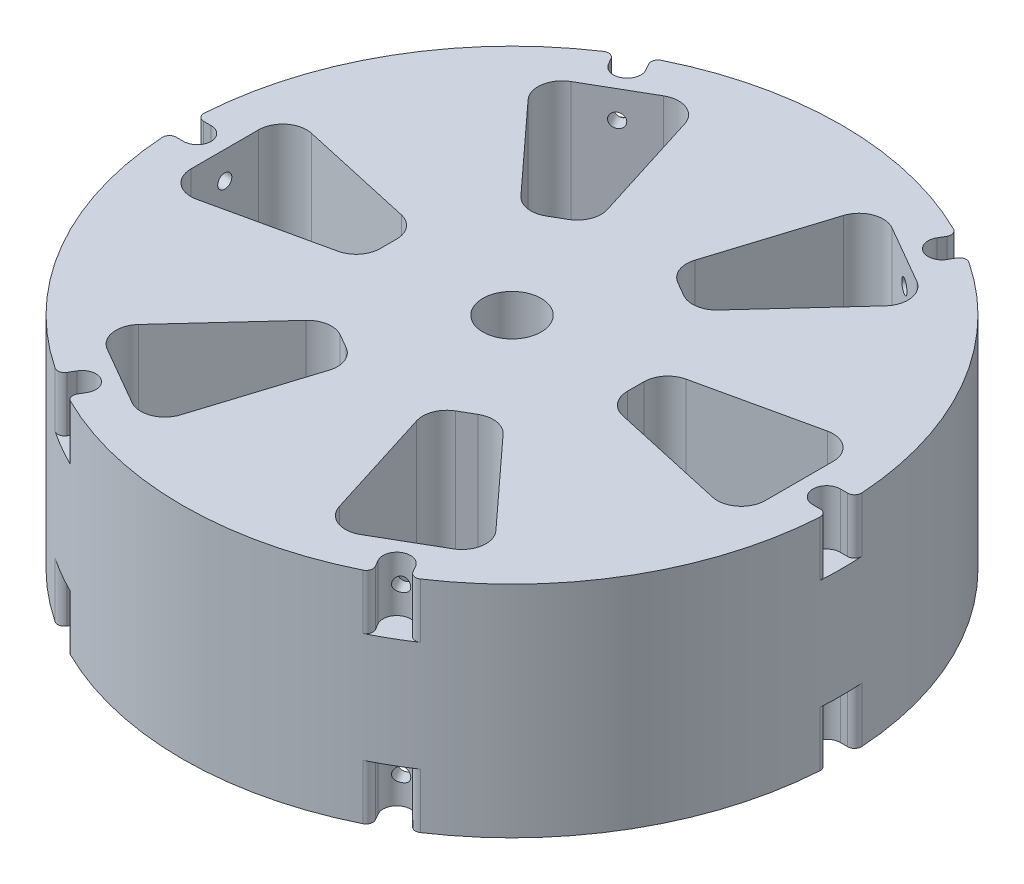
SolidWorks part; units mm, degrees
material "6061-T6 (SS)"
ref_plane "Front Plane" through (0, 0, 0) normal (0, 0, 1) x (1, 0, 0)
ref_plane "Top Plane" through (0, 0, 0) normal (0, 1, 0) x (1, 0, 0)
ref_plane "Right Plane" through (0, 0, 0) normal (1, 0, 0) x (0, 0, -1)
sketch "Sketch1" plane through (0, 0, 0) normal (0, 1, 0) x (1, 0, 0)
  circle A0 centre (0, 0) radius 76.2
  circle A1 centre (0, 0) radius 15.875
  dimension "D1" = 152.4
  dimension "D2" = 31.75
extrude "Boss-Extrude1" add sketch "Sketch1" against normal mid plane 50.8
sketch "Sketch3" plane through (0, -25.4, 0) normal (0, -1, 0) x (-1, 0, 0)
  line L0 (-76.1338, 3.175) -> (-72.771, 3.175)
  line L1 (-76.1338, -3.175) -> (-72.771, -3.175)
  circle A0 centre (0, 0) radius 76.2 construction
  arc A1 (-72.771, 3.175) -> (-72.771, -3.175) centre (-72.771, 0) cw
  arc A2 (-76.1338, -3.175) -> (-76.1338, 3.175) centre (0, 0) cw
  point P9 (-69.596, 0)
  point P13 (-76.2, 0)
  dimension "D1" = 6.35
  dimension "D2" = 6.604
extrude "Cut-Extrude1" cut sketch "Sketch3" against normal blind 12.7
sketch "Sketch4" plane through (0, -25.4, 0) normal (0, -1, 0) x (-1, 0, 0)
  line L0 (-66.421, 14.7602) -> (-66.421, -14.7602)
  line L1 (-66.421, -14.7602) -> (-28.575, -6.35)
  line L2 (-28.575, -6.35) -> (-28.575, 6.35)
  line L3 (-28.575, 6.35) -> (-66.421, 14.7602)
  line L4 (-66.421, 0) -> (0, 0) construction
  line L5 (-28.575, -6.35) -> (0, 0) construction
  circle A2 centre (0, 0) radius 15.875 construction
  point P12 (-15.875, 0)
  point P14 (-28.575, 0)
  dimension "D1" = 3.175
  dimension "D2" = 12.7
  dimension "D4" = 12.7
extrude "Cut-Extrude2" cut sketch "Sketch4" against normal through all
hole_wizard "#30 (0.1285) Diameter Hole1" positions "Sketch5" profile "Sketch6" hole size "#30" standard "ANSI Inch"
sketch "Sketch5" plane through (66.421, 0, 0) normal (-1, 0, 0) x (0, 0, 1)
  line L0 (-14.7602, -25.4) -> (14.7602, -25.4) construction
  point P0 (0, -19.05)
  dimension "D1" = 6.35
sketch "Sketch6" plane through (66.421, -19.05, 0) normal (0, 1, 0) x (0, 0, 1)
  line L0 (0, 0) -> (0, 9.779)
  line L1 (0, 9.779) -> (1.6319, 9.779)
  line L2 (1.6319, 9.779) -> (1.6319, 0)
  line L5 (1.6319, 0) -> (0, 0)
  line L11 (0, -6.35) -> (0, 107.95) construction
  dimension "Thru Hole Dia." = 3.2639
  dimension "Thru Hole Depth" = 9.779
fillet "Fillet1" radius 1.5875 2 edges at (76.1338, -19.05, 3.175) (76.1338, -19.05, -3.175)
fillet "Fillet2" radius 5.5562 4 edges at (66.421, 0, 14.7602) (66.421, 0, -14.7602) (28.575, 0, 6.35) (28.575, 0, -6.35)
mirror "Mirror1" about plane through (0, 0, 0) normal (0, 1, 0) of "Cut-Extrude1", "#30 (0.1285) Diameter Hole1"
pattern_circular "CirPattern1" count 6 over 360 about axis through (0, 0, 0) along (0, 1, 0) of "Cut-Extrude1", "Cut-Extrude2", "Fillet2", "Fillet1", "#30 (0.1285) Diameter Hole1", "Mirror1"
sketch "Sketch7" plane through (0, 25.4, 0) normal (0, 1, 0) x (1, 0, 0)
  circle A0 centre (0, 0) radius 6.7462
  circle A1 centre (0, 0) radius 15.875
  circle A2 centre (0, 0) radius 15.875 construction
  dimension "D1" = 13.4925
extrude "Boss-Extrude2" add sketch "Sketch7" against normal offset from surface (10.668 mm away) 40.132 up to face at (23.4912, -25.4, 40.6879)
fillet "Fillet3" radius 1.5875 12 edges at (76.1338, 19.05, 3.175) (76.1338, 19.05, -3.175) (35.3173, 19.05, -67.5213) (40.8165, 19.05, -64.3463) (-40.8165, 19.05, -64.3463) (-35.3173, 19.05, -67.5213) (-76.1338, 19.05, 3.175) (-76.1338, 19.05, -3.175) (-40.8165, 19.05, 64.3463) (-35.3173, 19.05, 67.5213) (35.3173, 19.05, 67.5213) (40.8165, 19.05, 64.3463)
sketch "Sketch8" plane through (0, -25.4, 0) normal (0, -1, 0) x (1, 0, 0)
  circle A0 centre (0, 0) radius 25.4
  dimension "D1" = 50.8
extrude "Cut-Extrude3" cut sketch "Sketch8" against normal blind 25.4
